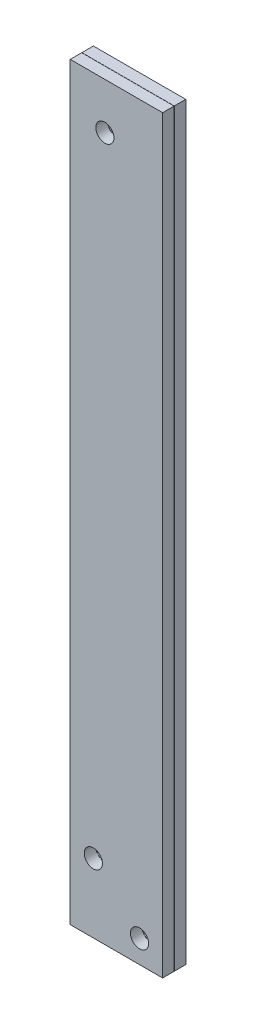
SolidWorks part; units mm, degrees
ref_plane "Alzado" through (0, 0, 0) normal (0, 0, 1) x (1, 0, 0)
ref_plane "Planta" through (0, 0, 0) normal (0, 1, 0) x (1, 0, 0)
ref_plane "Vista lateral" through (0, 0, 0) normal (1, 0, 0) x (0, 0, -1)
sketch "Croquis2" plane through (0, 0, 0) normal (0, 0, 1) x (1, 0, 0)
  line L0 (0, 0) -> (50.8, 0)
  line L1 (50.8, 0) -> (50.8, -361.2957)
  line L2 (50.8, -361.2957) -> (50.8, -412.0957)
  line L3 (50.8, -412.0957) -> (0, -412.0957)
  line L4 (0, -412.0957) -> (0, 0)
  dimension "D1" = 50.8
  dimension "D2" = 412.0957
extrude "Saliente-Extruir1" add sketch "Croquis2" along normal blind 6.31
sketch "Croquis3" plane through (50.8, 0, 0) normal (1, 0, 0) x (0, 0, -1)
  line L0 (-6.31, 0) -> (-6.41, 0)
  line L1 (-6.41, 0) -> (-12.72, 0)
  line L2 (-12.72, 0) -> (-12.72, -412.0957)
  line L3 (-12.72, -412.0957) -> (-6.41, -412.0957)
  line L4 (-6.41, 0) -> (-6.41, -412.0957)
  dimension "D1" = 0.1
  dimension "D2" = 6.31
extrude "Saliente-Extruir2" add sketch "Croquis3" against normal blind 50.8 separate body contours L4 L1 L2 L3
sketch "Croquis4" plane through (0, 0, 12.72) normal (0, 0, 1) x (1, 0, 0)
  line L0 (19.04, -25.4) -> (22.1587, -25.4) construction
  circle A0 centre (19.04, -25.4) radius 5
  dimension "D1" = 10
extrude "Cortar-Extruir1" cut sketch "Croquis4" against normal blind 31
sketch "Croquis5" plane through (0, 0, 12.72) normal (0, 0, 1) x (1, 0, 0)
  line L0 (16.6614, -377.213) -> (12.7, -374.1622) construction
  line L1 (12.7, -374.1622) -> (38.1, -399.5622) construction
  circle A0 centre (12.7, -374.1622) radius 5 construction
  circle A1 centre (12.7, -374.1622) radius 5
  circle A2 centre (38.1, -399.5622) radius 5
  dimension "D1" = 10
  dimension "D2" = 10
extrude "Cortar-Extruir2" cut sketch "Croquis5" against normal blind 35
